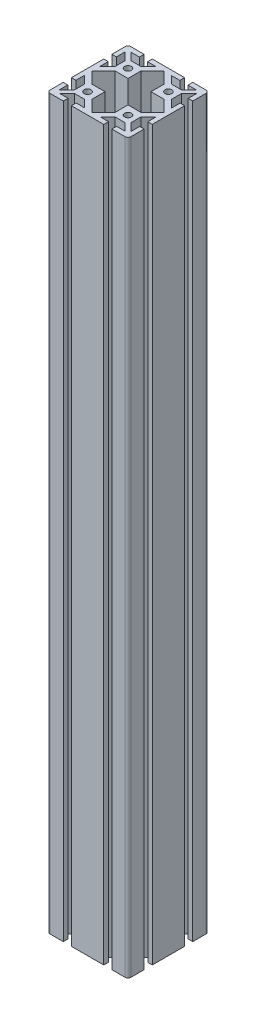
SolidWorks part; units mm, degrees
material "6063-T6"
ref_plane "Front Plane" through (0, 0, 0) normal (0, 0, 1) x (1, 0, 0)
ref_plane "Top Plane" through (0, 0, 0) normal (0, 1, 0) x (1, 0, 0)
ref_plane "Right Plane" through (0, 0, 0) normal (1, 0, 0) x (0, 0, -1)
sketch "Sketch1" plane through (0, 0, 0) normal (0, 0, 1) x (1, 0, 0)
  line L0 (0, 0) -> (0, 720)
  dimension "D1" = 720
other "80 series TS80-80M-650039(2)"
ref_plane "Plane2" through (0, 0, 0) normal (0, 1, 0) x (-1, 0, 0)
sketch "Sketch2" plane through (0, 0, 0) normal (0, 1, 0) x (-1, 0, 0)
  line L2 (-28, 15.179) -> (-28, 24.821)
  line L3 (-28, 24.821) -> (-35.5438, 32.3648)
  line L4 (-35.5438, 24) -> (-35.5438, 32.3648)
  line L5 (-37, 40) -> (-24, 40)
  line L6 (-40, 24) -> (-40, 37)
  line L7 (-24.821, 28) -> (-15.179, 28)
  line L8 (-24.821, 28) -> (-32.122, 35.301)
  line L9 (-32.122, 35.301) -> (-24, 35.301)
  line L10 (-15.179, 28) -> (-7.878, 35.301)
  line L11 (-16, 35.301) -> (-7.878, 35.301)
  line L12 (-24, 40) -> (-24, 35.301)
  line L13 (16, 40) -> (-16, 40)
  line L14 (-28, 15.179) -> (-35.5438, 7.6352)
  line L16 (-11.3534, 24.1744) -> (0, 35.5278)
  line L17 (28, 15.179) -> (28, 24.821)
  line L18 (35.5438, 16) -> (35.5438, 7.6352)
  line L19 (40, 16) -> (40, -16)
  line L20 (28, 15.179) -> (35.5438, 7.6352)
  line L21 (35.5278, 0) -> (24.1744, 11.3534)
  line L22 (24.1744, 11.3534) -> (11.3534, 11.3534)
  line L23 (-16, -40) -> (-16, -35.301)
  line L24 (-35.5438, -24) -> (-40, -24)
  line L25 (-35.5438, 16) -> (-40, 16)
  line L26 (-35.5438, 16) -> (-35.5438, 7.6352)
  line L27 (-35.5278, 0) -> (-24.1744, 11.3534)
  line L28 (-40, 16) -> (-40, -16)
  line L29 (-11.3534, -24.1744) -> (0, -35.5278)
  line L30 (-11.3534, 11.3534) -> (-11.3534, 24.1744)
  line L31 (-24.1744, 11.3534) -> (-11.3534, 11.3534)
  line L35 (16, 40) -> (16, 35.301)
  line L36 (35.5438, -16) -> (40, -16)
  line L37 (-15.179, -28) -> (-7.878, -35.301)
  line L38 (35.5438, 24) -> (40, 24)
  line L39 (24, 40) -> (24, 35.301)
  line L40 (32.122, 35.301) -> (24, 35.301)
  line L41 (24.821, 28) -> (32.122, 35.301)
  line L42 (11.3534, 11.3534) -> (11.3534, 24.1744)
  line L43 (40, 24) -> (40, 37)
  line L44 (37, 40) -> (24, 40)
  line L45 (35.5438, 24) -> (35.5438, 32.3648)
  line L46 (28, 24.821) -> (35.5438, 32.3648)
  line L47 (-11.3534, -11.3534) -> (-11.3534, -24.1744)
  line L48 (-24.1744, -11.3534) -> (-11.3534, -11.3534)
  line L49 (28, -24.821) -> (35.5438, -32.3648)
  line L50 (35.5438, -24) -> (35.5438, -32.3648)
  line L51 (24.821, 28) -> (15.179, 28)
  line L52 (37, -40) -> (24, -40)
  line L53 (11.3534, 24.1744) -> (0, 35.5278)
  line L54 (40, -24) -> (40, -37)
  line L55 (-24.821, -28) -> (-15.179, -28)
  line L56 (15.179, 28) -> (7.878, 35.301)
  line L57 (35.5438, 16) -> (40, 16)
  line L58 (24.821, -28) -> (32.122, -35.301)
  line L59 (-28, -15.179) -> (-28, -24.821)
  line L60 (-35.5438, 24) -> (-40, 24)
  line L61 (-16, 40) -> (-16, 35.301)
  line L62 (32.122, -35.301) -> (24, -35.301)
  line L63 (24, -40) -> (24, -35.301)
  line L64 (35.5438, -24) -> (40, -24)
  line L65 (16, -40) -> (16, -35.301)
  line L66 (-35.5438, -16) -> (-35.5438, -7.6352)
  line L67 (-28, -15.179) -> (-35.5438, -7.6352)
  line L69 (-35.5278, 0) -> (-24.1744, -11.3534)
  line L70 (24.821, -28) -> (15.179, -28)
  line L71 (28, -15.179) -> (28, -24.821)
  line L72 (35.5438, -16) -> (35.5438, -7.6352)
  line L73 (-35.5438, -16) -> (-40, -16)
  line L74 (28, -15.179) -> (35.5438, -7.6352)
  line L75 (35.5278, 0) -> (24.1744, -11.3534)
  line L76 (24.1744, -11.3534) -> (11.3534, -11.3534)
  line L77 (11.3534, -11.3534) -> (11.3534, -24.1744)
  line L78 (15.179, -28) -> (7.878, -35.301)
  line L79 (16, -35.301) -> (7.878, -35.301)
  line L80 (11.3534, -24.1744) -> (0, -35.5278)
  line L81 (16, -40) -> (-16, -40)
  line L82 (-24, -40) -> (-24, -35.301)
  line L83 (-16, -35.301) -> (-7.878, -35.301)
  line L84 (-32.122, -35.301) -> (-24, -35.301)
  line L85 (-24.821, -28) -> (-32.122, -35.301)
  line L86 (-40, -24) -> (-40, -37)
  line L87 (-37, -40) -> (-24, -40)
  line L88 (-35.5438, -24) -> (-35.5438, -32.3648)
  line L89 (-28, -24.821) -> (-35.5438, -32.3648)
  line L90 (16, 35.301) -> (7.878, 35.301)
  arc A0 (-37, 40) -> (-40, 37) centre (-37, 37) ccw
  arc A1 (37, 40) -> (40, 37) centre (37, 37) cw
  circle A2 centre (20, -20) radius 3.35
  circle A3 centre (-20, -20) radius 3.35
  arc A4 (37, -40) -> (40, -37) centre (37, -37) ccw
  arc A5 (-37, -40) -> (-40, -37) centre (-37, -37) cw
  circle A6 centre (-20, 20) radius 3.35
  circle A7 centre (20, 20) radius 3.35
  point P1 (-40, 40)
  point P3 (-20, 40)
  point P10 (20, 40)
  point P34 (0, 40)
  point P38 (-20, 28)
  point P51 (0, 0)
  point P61 (40, 40)
  point P62 (40, 20)
  point P74 (-28, 20)
  point P76 (40, -20)
  point P77 (20, -40)
  point P96 (-40, 0)
  point P98 (40, 0)
  point P106 (0, -40)
  point P114 (-20, -40)
  point P115 (40, -40)
  point P116 (-40, -40)
  point P117 (-40, -20)
  point P118 (-40, 20)
  point P119 (0, 0)
  dimension "D1" = 6.7
hole_wizard "M8x1.25 Tapped Hole2" positions "Sketch3" profile "Sketch4" tap size "M8x1.25" standard "ANSI Metric"
sketch "Sketch3" plane through (0, 0, 0) normal (0, -1, 0) x (-1, 0, 0)
  point P0 (-20, 20)
  point P3 (20, 20)
  point P6 (20, -20)
  point P9 (-20, -20)
sketch "Sketch4" plane through (20, 0, -20) normal (1, 0, 0) x (0, 0, -1)
  line L0 (0, 0) -> (0, 27.0429)
  line L1 (0, 27.0429) -> (3.4, 25)
  line L2 (3.4, 25) -> (3.4, 0)
  line L5 (3.4, 0) -> (0, 0)
  line L10 (0, 27.0429) -> (-3.4, 25) construction
  line L11 (0, -6.35) -> (0, 107.95) construction
  dimension "Tap Drill Dia." = 6.8
  dimension "Tap Drill Depth" = 25
  dimension "Drill Angle" = 118
cosmetic thread "Hole Thread1" parameters "D1"=20, "D2"=8
cosmetic thread "Hole Thread2" parameters "D1"=20, "D2"=8
cosmetic thread "Hole Thread3" parameters "D1"=20, "D2"=8
cosmetic thread "Hole Thread4" parameters "D1"=20, "D2"=8
hole_wizard "M8x1.25 Tapped Hole3" positions "Sketch5" profile "Sketch6" tap size "M8x1.25" standard "ANSI Metric"
sketch "Sketch5" plane through (0, 720, 0) normal (0, 1, 0) x (1, 0, 0)
  point P0 (-20, -20)
sketch "Sketch6" plane through (-20, 720, 20) normal (1, 0, 0) x (0, 0, 1)
  line L0 (0, 0) -> (0, 27.0429)
  line L1 (0, 27.0429) -> (3.4, 25)
  line L2 (3.4, 25) -> (3.4, 0)
  line L5 (3.4, 0) -> (0, 0)
  line L10 (0, 27.0429) -> (-3.4, 25) construction
  line L11 (0, -6.35) -> (0, 107.95) construction
  dimension "Tap Drill Dia." = 6.8
  dimension "Tap Drill Depth" = 25
  dimension "Drill Angle" = 118
cosmetic thread "Hole Thread5" parameters "D1"=20, "D2"=8
